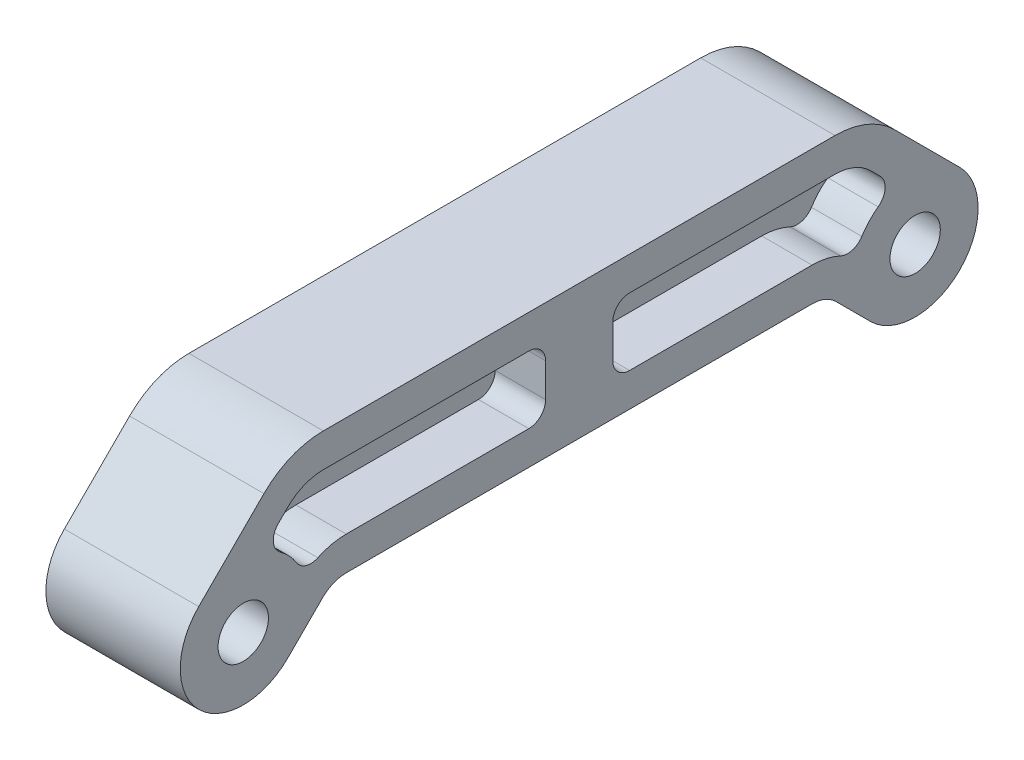
SolidWorks part; units mm, degrees
ref_plane "前视基准面" through (0, 0, 0) normal (0, 0, 1) x (1, 0, 0)
ref_plane "上视基准面" through (0, 0, 0) normal (0, 1, 0) x (1, 0, 0)
ref_plane "右视基准面" through (0, 0, 0) normal (1, 0, 0) x (0, 0, -1)
sketch "草图1" plane through (0, 0, 0) normal (1, 0, 0) x (0, 0, -1)
  line L0 (0, 0) -> (40, 0) construction
  line L1 (2.6517, -2.6517) -> (5.3033, 0)
  line L2 (5.3033, 0) -> (34.6967, 0)
  line L3 (34.6967, 0) -> (37.3483, -2.6517)
  line L4 (-2.6517, 2.6517) -> (2.6967, 8)
  line L5 (2.6967, 8) -> (37.3033, 8)
  line L6 (37.3033, 8) -> (42.6517, 2.6517)
  circle A0 centre (0, 0) radius 1.5
  arc A1 (37.3483, -2.6517) -> (42.6517, 2.6517) centre (40, 0) ccw
  arc A2 (-2.6517, 2.6517) -> (2.6517, -2.6517) centre (0, 0) ccw
  circle A3 centre (40, 0) radius 1.5
  dimension "D2" = 3
  dimension "D3" = 7.5
  dimension "D4" = 45
  dimension "D1" = 40
  dimension "D5" = 45
  dimension "D6" = 8
extrude "凸台-拉伸1" add sketch "草图1" along normal mid plane 8
fillet "圆角1" radius 2 2 edges at (0, 0, -34.6967) (0, 0, -5.3033)
fillet "圆角2" radius 5 2 edges at (0, 8, -37.3033) (0, 8, -2.6967)
sketch "草图2" plane through (4, 0, 0) normal (1, 0, 0) x (0, 0, -1)
  line L6 (18, 6) -> (18, 2)
  line L7 (22, 2) -> (22, 6)
  line L8 (18, 6) -> (4.7678, 6)
  line L9 (22, 2) -> (33.8683, 2)
  line L12 (41.2374, 1.2374) -> (37.3536, 5.1213)
  line L13 (35.2322, 6) -> (4.7678, 6)
  line L14 (2.6464, 5.1213) -> (-1.2374, 1.2374)
  line L15 (1.2374, -1.2374) -> (3.3033, 0.8284)
  line L16 (6.1317, 2) -> (33.8683, 2)
  line L17 (36.6967, 0.8284) -> (38.7626, -1.2374)
  line L18 (38.8922, 3.5826) -> (37.3536, 5.1213)
  line L19 (35.2322, 6) -> (22, 6)
  line L20 (2.6464, 5.1213) -> (1.1078, 3.5826)
  line L22 (6.1317, 2) -> (18, 2)
  arc A6 (3.5888, 1.0876) -> (1.1078, 3.5826) centre (0, 0) ccw
  arc A7 (38.8922, 3.5826) -> (36.4112, 1.0876) centre (40, 0) ccw
  arc A8 (37.3483, -2.6517) -> (42.6517, 2.6517) centre (40, 0) ccw construction
  arc A9 (-2.6517, 2.6517) -> (2.6517, -2.6517) centre (0, 0) ccw construction
  circle A10 centre (0, 0) radius 1.5 construction
  arc A12 (37.3536, 5.1213) -> (35.2322, 6) centre (35.2322, 3) ccw
  arc A13 (4.7678, 6) -> (2.6464, 5.1213) centre (4.7678, 3) ccw
  arc A14 (-1.2374, 1.2374) -> (1.2374, -1.2374) centre (0, 0) ccw
  arc A15 (6.1317, 2) -> (3.3033, 0.8284) centre (6.1317, -2) ccw
  arc A16 (36.6967, 0.8284) -> (33.8683, 2) centre (33.8683, -2) ccw
  arc A17 (38.7626, -1.2374) -> (41.2374, 1.2374) centre (40, 0) ccw
  arc A18 (37.3536, 5.1213) -> (35.2322, 6) centre (35.2322, 3) ccw
  arc A19 (4.7678, 6) -> (2.6464, 5.1213) centre (4.7678, 3) ccw
  arc A21 (6.1317, 2) -> (3.5888, 1.0876) centre (6.1317, -2) ccw
  arc A22 (36.4112, 1.0876) -> (33.8683, 2) centre (33.8683, -2) ccw
  dimension "D2" = 4
  dimension "D3" = 18
  dimension "D1" = 2
extrude "切除-拉伸1" cut sketch "草图2" against normal blind 3
mirror "镜向1" about plane through (0, 0, 0) normal (1, 0, 0) of "切除-拉伸1"
fillet "圆角3" radius 1 16 edges at (-2.5, 2, -22) (-2.5, 3.5826, -38.8922) (-2.5, 1.0876, -36.4112) (-2.5, 6, -22) (-2.5, 2, -18) (-2.5, 1.0876, -3.5888) (-2.5, 3.5826, -1.1078) (-2.5, 6, -18) (2.5, 3.5826, -1.1078) (2.5, 2, -18) (2.5, 6, -18) (2.5, 1.0876, -36.4112) (2.5, 3.5826, -38.8922) (2.5, 6, -22) (2.5, 2, -22) (2.5, 1.0876, -3.5888)
